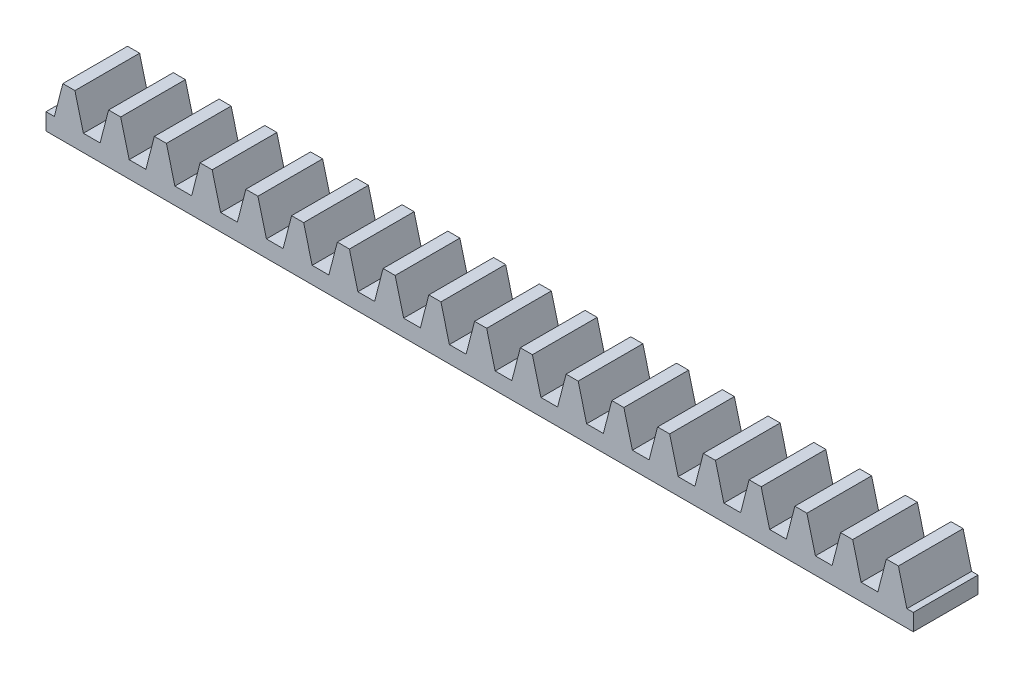
SolidWorks part; units mm, degrees
extrude "Blank" add sketch "BlankSke" against normal blind 5
sketch "BlankSke" plane through (0, 0, 0) normal (0, 0, 1) x (1, 0, 0)
  line L1 (0, 0) -> (67, 0)
  line L2 (0, 0) -> (0, 5.125)
  line L3 (0, 5.125) -> (67, 5.125)
  line L4 (67, 0) -> (67, 5.125)
  dimension "Length" = 67
  dimension "Blank_height" = 5.125
ref_plane "Plane1" through (0, 0, 0) normal (0, 0, 1) x (1, 0, 0)
ref_plane "Plane2" through (0, 0, 0) normal (0, 1, 0) x (1, 0, 0)
ref_plane "Plane3" through (0, 0, 0) normal (1, 0, 0) x (0, 0, -1)
sketch "HoldingSke" plane through (0, 0, 0) normal (0, 1, 0) x (1, 0, 0)
  line L0 (0, 0) -> (0.1237, 0.8802)
  line L1 (-15, 0) -> (100, 0) construction
  line L2 (0, 0) -> (-2.1039, 2.3779)
  line L3 (0, 0) -> (-11.863, 4.5341)
  line L4 (0, 0) -> (8.1152, 2.9537)
  line L5 (0, 0) -> (-23.7986, -8.8762)
  line L6 (0, 0) -> (-10.5278, -7.1032)
  line L9 (-67.7845, 28.3722) -> (-2.9186, 45.1477)
  line L10 (-76.2, 3.5029) -> (-72.2, 3.5029)
  line L11 (0, 0) -> (-5, 0)
  line L12 (-76.2, 101.6) -> (-76.158, 101.6)
  line L13 (24.9733, 27.94) -> (52.9518, 28.4284)
  line L14 (24.9733, 27.94) -> (24.9743, 27.94)
  line L15 (24.9733, 27.94) -> (100.4006, 29.5858)
  circle A0 centre (0, 0) radius 19.05
  circle A1 centre (0, 0) radius 2
  circle A2 centre (0, 0) radius 12.7
  dimension "MPH" = 4
  dimension "Diameter" = 38.1
  dimension "Num_teeth" = 20
  dimension "Pitch" = 0.8889
  dimension "Show_teeth" = 998
  dimension "Thickness" = 12.7
  dimension "Ap" = 14.5
  dimension "Pitch_height" = 4
  dimension "Width" = 5
  dimension "Backlash" = 0.042
  dimension "Addendum_fac" = 1
  dimension "Dedendum_fac" = 1.25
  dimension "Clearance_fac" = 0.25
  dimension "Dedendum_add" = 0.001
  dimension "Length" = 67
  dimension "Module" = 1.125
sketch "TooCutSkeIll" plane through (0, 0, 0) normal (0, 0, 1) x (1, 0, 0)
  line L0 (-1.2918, 5.0913) -> (-0.7006, 2.8053)
  line L1 (-0.4274, 2.5938) -> (0.4274, 2.5938)
  line L2 (0.7006, 2.8053) -> (1.2918, 5.0913)
  line L3 (67, 5.125) -> (0, 5.125) construction
  line L4 (0, 0) -> (0, 64.897) construction
  line L5 (-13.208, 4) -> (12.954, 4) construction
  line L6 (0, 0) -> (67, 0) construction
  line L7 (1.0096, 4) -> (1.0096, 48.7463) construction
  line L8 (-1.0096, 4) -> (-1.0096, 48.7463) construction
  line L9 (1.3354, 5.125) -> (1.3354, 5.1504)
  line L10 (-1.3354, 5.125) -> (-1.3354, 5.1504)
  line L11 (-1.3354, 5.1504) -> (1.3354, 5.1504)
  arc A0 (0.4274, 2.5938) -> (0.7006, 2.8053) centre (0.4274, 2.876) ccw
  arc A1 (-0.7006, 2.8053) -> (-0.4274, 2.5938) centre (-0.4274, 2.876) ccw
  arc A2 (1.3354, 5.125) -> (1.2918, 5.0913) centre (1.3354, 5.08) ccw
  arc A3 (-1.2918, 5.0913) -> (-1.3354, 5.125) centre (-1.3354, 5.08) ccw
  dimension "Pitch_height" = 4
  dimension "Addendum_plus" = 1.1504
  dimension "Pressure_angle" = 14.5
  dimension "Gap_width" = 2.0191
  dimension "Dedendum" = 1.4062
extrude "ToothCutIll" [suppressed] cut sketch "TooCutSkeIll" against normal through all
sketch "TooCutSkeSim" plane through (0, 0, 0) normal (0, 0, 1) x (1, 0, 0)
  line L0 (0.6459, 2.5937) -> (-0.6459, 2.5937)
  line L1 (1.3071, 5.1504) -> (0.6459, 2.5937)
  line L2 (0, 17.4625) -> (0, 53.467) construction
  line L3 (1.3071, 5.1504) -> (-1.3071, 5.1504)
  line L6 (-1.3071, 5.1504) -> (-0.6459, 2.5937)
  line L9 (-1.0096, 4) -> (1.0096, 4) construction
  line L10 (0, 0) -> (67, 0) construction
  line L11 (1.0096, 4) -> (1.0096, 53.467) construction
  line L12 (-1.0096, 4) -> (-1.0096, 53.467) construction
  dimension "Pitch_height" = 4
  dimension "Addendum_plus" = 1.1504
  dimension "Pressure_angle" = 14.5
  dimension "Gap_width" = 2.0191
  dimension "Dedendum" = 1.4062
extrude "ToothCutSim" cut sketch "TooCutSkeSim" against normal through all
pattern_linear "TeethCuts" count 20 spacing 3.5343 along (1, 0, 0) of "ToothCutIll", "ToothCutSim"
sketch "Croquis1" plane through (0, 0, 0) normal (0, 0, 1) x (1, 0, 0)
  line L0 (67, 0) -> (67, 2.5937) construction
  line L1 (0, 0) -> (67, 0)
  line L2 (0, 0) -> (0, 1.2969)
  line L3 (0, 1.2969) -> (67, 1.2969)
  line L4 (67, 0) -> (67, 1.2969)
extrude "Cortar-Extruir1" cut sketch "Croquis1" against normal blind 10
equation "' \"Module@HoldingSke\" = 6.35"
equation "' \"Num_teeth@HoldingSke\" = 12"
equation "' \"Ap@HoldingSke\" =  20"
equation "' \"Ap@HoldingSke\" = 20"
equation "' \"Width@HoldingSke\" = 0.25 * 25.4"
equation "' \"Show_teeth@HoldingSke\" = 500"
equation "' \"Backlash@HoldingSke\" = 0.009 * 25.4"
equation "' \"Addendum_fac@HoldingSke\" = 1.0"
equation "' \"Dedendum_fac@HoldingSke\" = 1.25"
equation "' \"Dedendum_add@HoldingSke\" = 0.00005 * 25.4"
equation "' \"Clearance_fac@HoldingSke\" = 0.25"
equation "' \"Pitch_height@HoldingSke\" = 1 * 25.4"
equation "' \"Length@HoldingSke\" = 4.71 * 25.4"
equation "\"Pitch@HoldingSke\" = 1 / \"Module@HoldingSke\""
equation "\"MPH@HoldingSke\" = \"Dedendum_fac@HoldingSke\" / \"Pitch@HoldingSke\" + 2 * \"Dedendum_add@HoldingSke\" + 0.002 * 25.4"
equation "\"MPH@HoldingSke\" = ((sgn( \"MPH@HoldingSke\" - \"Pitch_height@HoldingSke\")+1)*( \"MPH@HoldingSke\" - \"Pitch_height@HoldingSke\"))/2 + \"Pitch_height@HoldingSke\""
equation "\"Blank_height@BlankSke\" = \"Pitch_height@HoldingSke\" + \"Addendum_fac@HoldingSke\"  / \"Pitch@HoldingSke\" "
equation "\"Length@BlankSke\" =  \"Length@HoldingSke\""
equation "\"Face_width@Blank\" = \"Width@HoldingSke\""
equation "\"Pressure_angle@TooCutSkeIll\" = \"Ap@HoldingSke\""
equation "\"Addendum_plus@TooCutSkeIll\" =  \"Addendum_fac@HoldingSke\"  / \"Pitch@HoldingSke\" + 0.001 *25.4"
equation "\"Dedendum@TooCutSkeIll\" = \"Dedendum_fac@HoldingSke\"  / \"Pitch@HoldingSke\""
equation "\"Pitch_height@TooCutSkeIll\" =  \"MPH@HoldingSke\""
equation "\"Gap_width@TooCutSkeIll\" = 3.14159265 / 2 / \"Pitch@HoldingSke\" + 6 * \"Backlash@HoldingSke\""
equation "\"Pressure_angle@TooCutSkeSim\" = \"Ap@HoldingSke\""
equation "\"Addendum_plus@TooCutSkeSim\" =  \"Addendum_fac@HoldingSke\"  / \"Pitch@HoldingSke\" + 0.001 * 25.4"
equation "\"Dedendum@TooCutSkeSim\" = \"Dedendum_fac@HoldingSke\"  / \"Pitch@HoldingSke\""
equation "\"Pitch_height@TooCutSkeSim\" =  \"MPH@HoldingSke\""
equation "\"Gap_width@TooCutSkeSim\" = 3.14159265 / 2 / \"Pitch@HoldingSke\" + 6 * \"Backlash@HoldingSke\""
equation "\"Root_fillet@TooCutSkeIll\" = \"Clearance_fac@HoldingSke\" / \"Pitch@HoldingSke\" + \"Dedendum_add@HoldingSke\""
equation "\"Break_rad@TooCutSkeIll\" = 0.02 / \"Pitch@HoldingSke\" * 2"
equation "\"Linear_pitch@TeethCuts\" = 3.14159265 / \"Pitch@HoldingSke\""
equation "\"Num_teeth@HoldingSke\" = int( ( \"Length@HoldingSke\" + 0 ) / (3.14159265 / \"Pitch@HoldingSke\")) + 0.9999  + 1"
equation " \"Num_teeth@TeethCuts\" = int( \"Show_teeth@HoldingSke\" ) + 1"
equation " \"Num_teeth@TeethCuts\" = ((sgn( \"Num_teeth@TeethCuts\" - \"Num_teeth@HoldingSke\" )-1)*( \"Num_teeth@TeethCuts\" - \"Num_teeth@HoldingSke\" ))/-2+ \"Num_teeth@HoldingSke\""
equation " \"Num_teeth@TeethCuts\" = ((sgn( \"Num_teeth@TeethCuts\" - 2.0)+1)*( \"Num_teeth@TeethCuts\" - 2.0))/2 +2.0"
